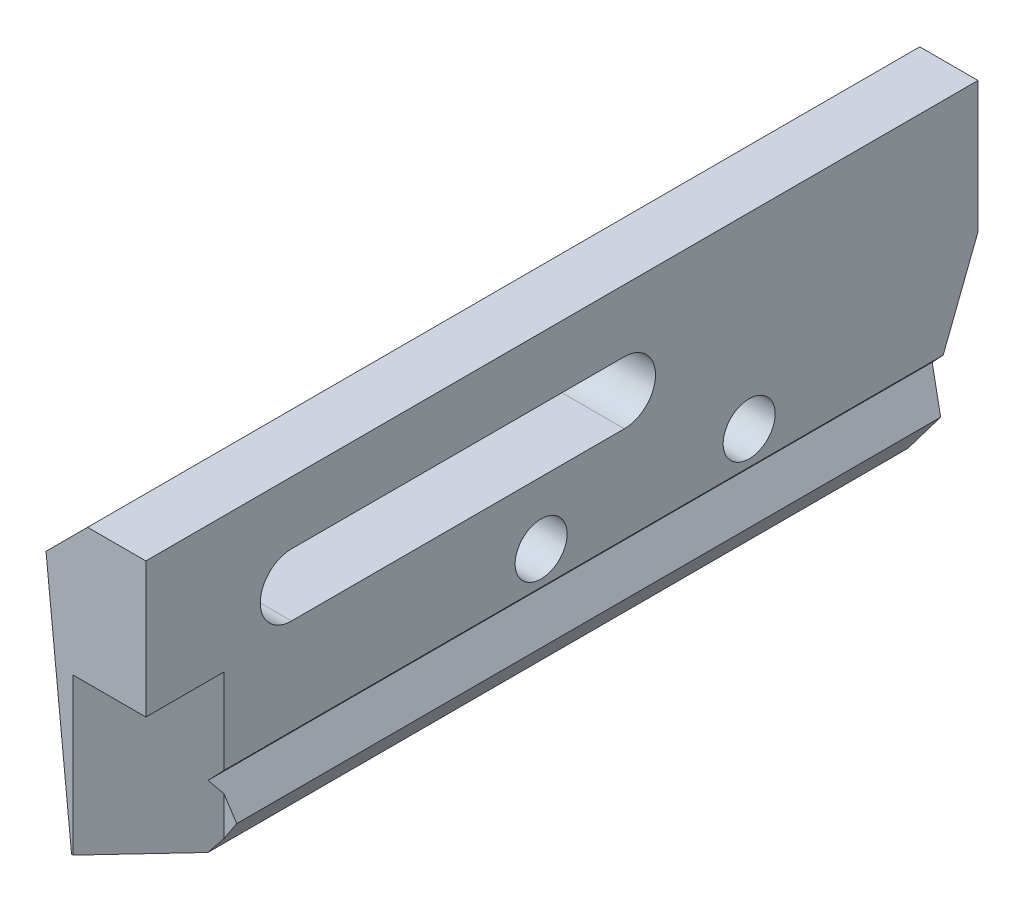
SolidWorks part; units mm, degrees
ref_plane "Plan de face" through (0, 0, 0) normal (0, 0, 1) x (1, 0, 0)
ref_plane "Plan de dessus" through (0, 0, 0) normal (0, 1, 0) x (1, 0, 0)
ref_plane "Plan de droite" through (0, 0, 0) normal (1, 0, 0) x (0, 0, -1)
sketch "Esquisse1" plane through (0, 0, 0) normal (0, 0, 1) x (1, 0, 0)
  line L0 (0, -2) -> (2, 0)
  line L1 (2, 0) -> (4.8, 0)
  line L3 (1.23, -14) -> (4.43, -14)
  line L4 (4.8, 0) -> (4.8, -10.6)
  line L6 (4.43, -11) -> (5.42, -12.5)
  line L7 (5.42, -12.5) -> (4.43, -14)
  line L8 (0, -2) -> (1.23, -14)
  line L9 (4.43, -11) -> (4.8, -10.6)
  point P0 (0, 0)
  dimension "D1" = 4.8
  dimension "D2" = 3.2
  dimension "D6" = 12
  dimension "D5" = 2
  dimension "D3" = 4.19
  dimension "D4" = 2.8
  dimension "D7" = 1.5
  dimension "D8" = 3
  dimension "D9" = 10.6
extrude "Boss.-Extru.1" add sketch "Esquisse1" along normal blind 40
sketch "Esquisse2" plane through (4.8, 0, 0) normal (1, 0, 0) x (0, 0, -1)
  line L0 (0, -10.6) -> (0, 0) construction
  line L1 (0, -14) -> (0, -6.3)
  line L2 (0, -6.3) -> (-3, -14)
  line L3 (-40, -14) -> (0, -14) construction
  line L4 (-3, -14) -> (0, -14)
  line L5 (-40, 0) -> (0, 0) construction
  dimension "D1" = 6.3
  dimension "D2" = 3
extrude "Enlèv. mat.-Extru.1" cut sketch "Esquisse2" against normal through all and the other way through all
ref_plane "Plan1" through (0, -6.5, 0) normal (0, 1, 0) x (-1, 0, 0)
sketch "Esquisse3" plane through (0, -6.5, 0) normal (0, 1, 0) x (-1, 0, 0)
  line L0 (-4.8, 40) -> (-2, 40) construction
  line L1 (-6.8, 40) -> (-1.3, 40)
  line L3 (-6.8, 40) -> (-6.8, 36.25)
  line L4 (-1.3, 40) -> (-4.8, 36.25)
  line L5 (-4.8, 36.25) -> (-6.8, 36.25)
  dimension "D1" = 3.5
  dimension "D2" = 3.75
  dimension "D3" = 2
extrude "Enlèv. mat.-Extru.3" cut sketch "Esquisse3" against normal blind 40
hole_wizard "Trou taraudé M31" positions "Esquisse5" profile "Esquisse4" tap size "M3" standard "ISO"
sketch "Esquisse5" plane through (4.8, 0, 0) normal (1, 0, 0) x (0, 0, -1)
  line L0 (0, -6.3) -> (0, 0) construction
  line L1 (-40, 0) -> (0, 0) construction
  point P0 (-11, -9)
  point P1 (-21, -9)
  dimension "D1" = 10
  dimension "D2" = 11
  dimension "D3" = 9
sketch "Esquisse4" plane through (4.8, -9, 11) normal (0, 1, 0) x (0, 0, -1)
  line L0 (0, 0) -> (0, 9.2511)
  line L1 (0, 9.2511) -> (1.25, 8.5)
  line L2 (1.25, 8.5) -> (1.25, 0)
  line L5 (1.25, 0) -> (0, 0)
  line L10 (0, 9.2511) -> (-1.25, 8.5) construction
  line L11 (0, -6.35) -> (0, 107.95) construction
  dimension "Diamètre du trou pour taraudage" = 2.5
  dimension "Profondeur du trou pour taraudage" = 8.5
  dimension "Angle de pointe" = 118
cosmetic thread "Filetage de perçage1" parameters "D1"=4.2106, "D2"=3
cosmetic thread "Filetage de perçage2" parameters "D1"=4.2106, "D2"=3
sketch "Esquisse6" plane through (4.8, 0, 0) normal (1, 0, 0) x (0, 0, -1)
  line L0 (-33, -4.5) -> (-17, -4.5) construction
  line L1 (-33, -3) -> (-17, -3)
  line L2 (-33, -6) -> (-17, -6)
  line L3 (-40, -6.5) -> (-40, 0) construction
  line L4 (-40, 0) -> (0, 0) construction
  arc A0 (-33, -3) -> (-33, -6) centre (-33, -4.5) ccw
  arc A1 (-17, -6) -> (-17, -3) centre (-17, -4.5) ccw
  point P2 (-25, -4.5)
  dimension "D1" = 1.5
  dimension "D3" = 7
  dimension "D2" = 16
  dimension "D4" = 3
extrude "Enlèv. mat.-Extru.4" cut sketch "Esquisse6" against normal blind 3.6
